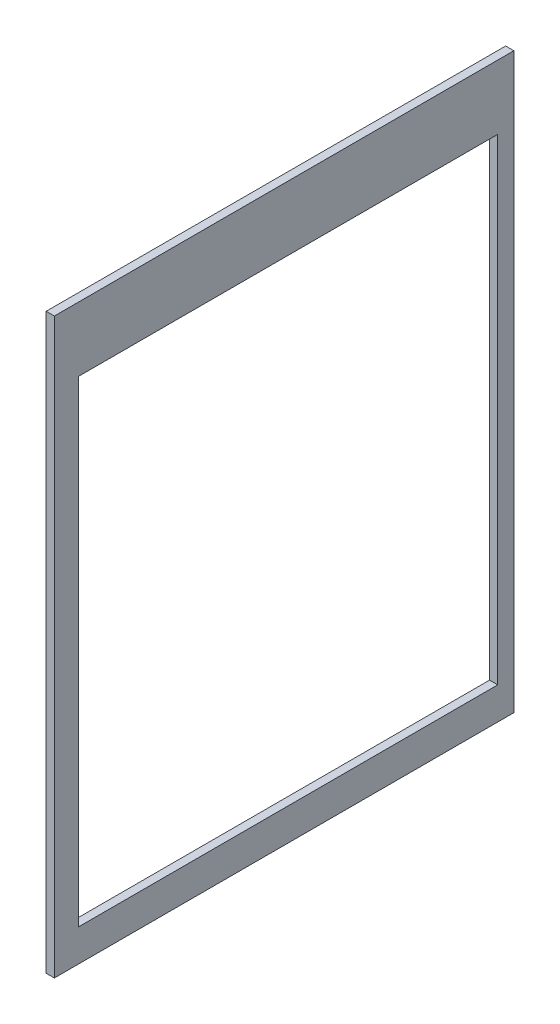
SolidWorks part; units mm, degrees
ref_plane "Alzado" through (0, 0, 0) normal (0, 0, 1) x (1, 0, 0)
ref_plane "Planta" through (0, 0, 0) normal (0, 1, 0) x (1, 0, 0)
ref_plane "Vista lateral" through (0, 0, 0) normal (1, 0, 0) x (0, 0, -1)
sketch "Croquis1" plane through (0, 0, 0) normal (1, 0, 0) x (0, 0, -1)
  line L8 (-389.3217, 326.7825) -> (-108.8217, 326.7825)
  line L11 (-389.3217, 326.7825) -> (-389.3217, -23.2175)
  line L17 (-389.3217, -23.2175) -> (-108.8217, -23.2175)
  line L39 (-108.8217, 326.7825) -> (-108.8217, -23.2175)
  line L40 (-118.6466, -3.5677) -> (-374.5844, -3.5677)
  line L41 (-118.6466, -3.5677) -> (-118.6466, 287.4831)
  line L42 (-118.6466, 287.4831) -> (-374.5844, 287.4831)
  line L43 (-374.5844, -3.5677) -> (-374.5844, 287.4831)
  dimension "D1" = 39.2995
  dimension "D2" = 19.6497
  dimension "D3" = 350
  dimension "D4" = 255.9378
extrude "Saliente-Extruir2" add sketch "Croquis1" along normal blind 5
